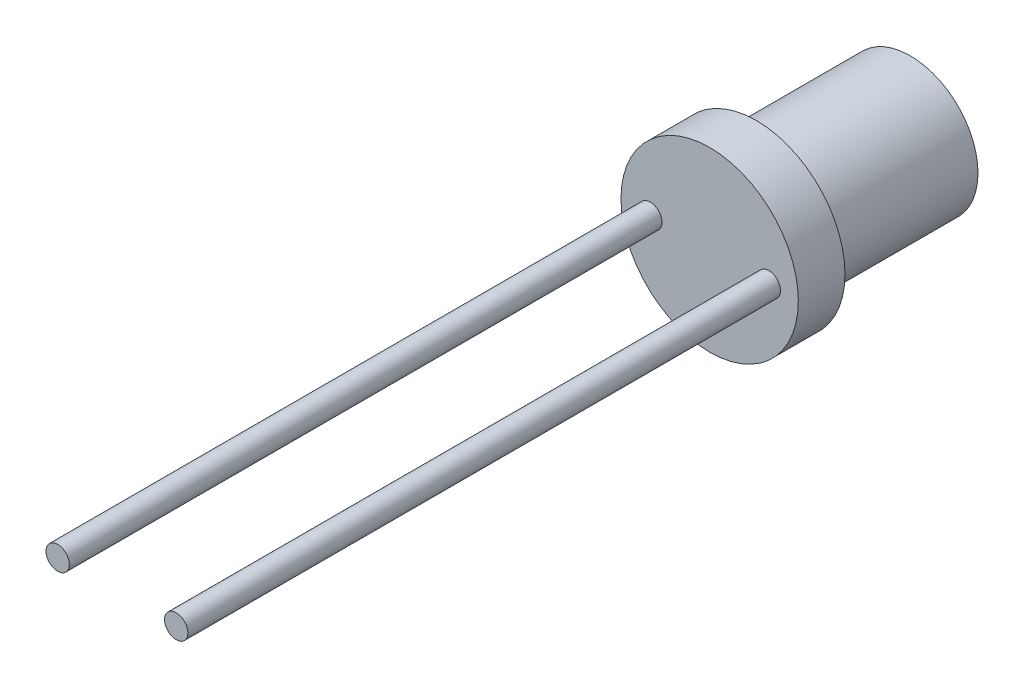
SolidWorks part; units mm, degrees
ref_plane "前视基准面" through (0, 0, 0) normal (0, 0, 1) x (1, 0, 0)
ref_plane "上视基准面" through (0, 0, 0) normal (0, 1, 0) x (1, 0, 0)
ref_plane "右视基准面" through (0, 0, 0) normal (1, 0, 0) x (0, 0, -1)
sketch "草图1" plane through (0, 0, 0) normal (0, 0, 1) x (1, 0, 0)
  circle A0 centre (0, 0) radius 1.45
  dimension "D1" = 2.9
extrude "拉伸1" add sketch "草图1" along normal blind 3.3
sketch "草图2" plane through (0, 0, 3.3) normal (0, 0, 1) x (1, 0, 0)
  circle A0 centre (0, 0) radius 1.9
  dimension "D1" = 3.8
extrude "拉伸2" add sketch "草图2" along normal blind 1
sketch "草图3" plane through (0, 0, 4.3) normal (0, 0, 1) x (1, 0, 0)
  line L0 (0, 2.011) -> (0, -2.1052) construction
  line L1 (-2.1813, 0) -> (2.3335, 0) construction
  circle A0 centre (-1.27, 0) radius 0.25
  circle A1 centre (1.27, 0) radius 0.25
  dimension "D1" = 0.5
  dimension "D2" = 2.54
extrude "拉伸3" add sketch "草图3" along normal blind 12.7
